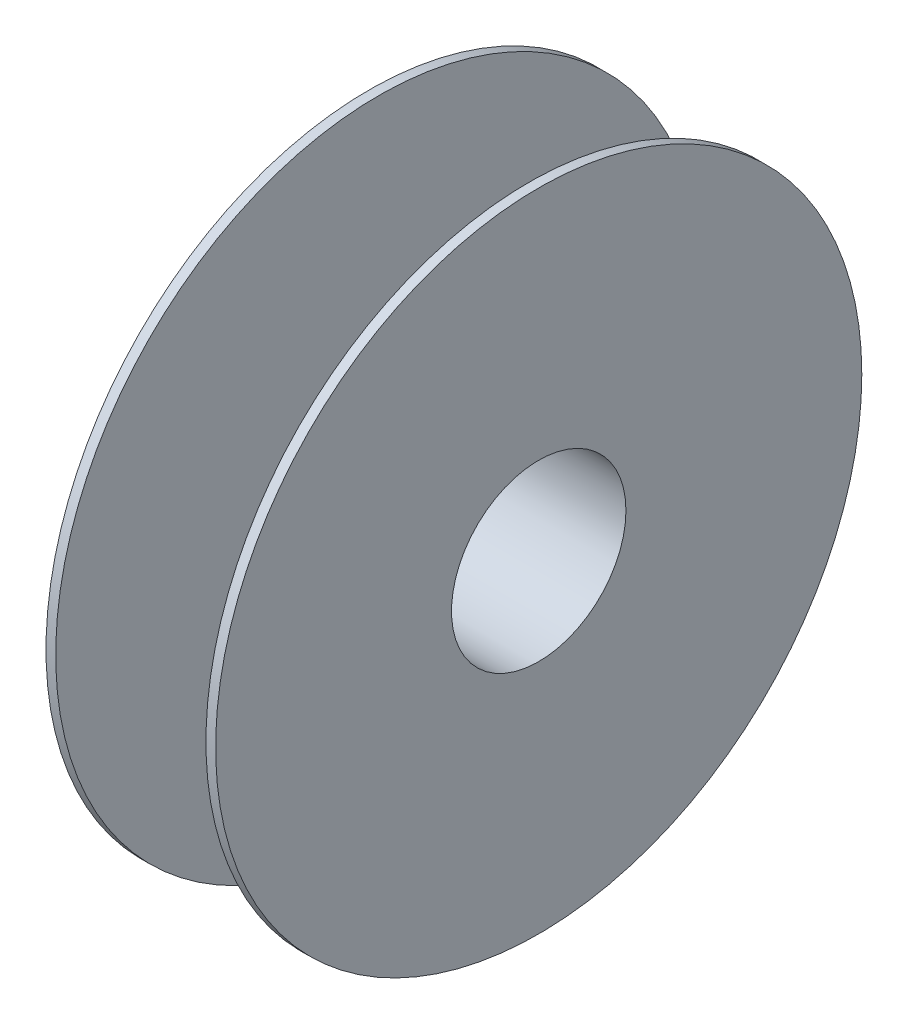
SolidWorks part; units mm, degrees
ref_plane "Front Plane" through (0, 0, 0) normal (0, 0, 1) x (1, 0, 0)
ref_plane "Top Plane" through (0, 0, 0) normal (0, 1, 0) x (1, 0, 0)
ref_plane "Right Plane" through (0, 0, 0) normal (1, 0, 0) x (0, 0, -1)
sketch "Sketch1" plane through (0, 0, 0) normal (0, 0, 1) x (1, 0, 0)
  line L0 (-26.25, 27) -> (-26.25, 100)
  line L1 (-26.25, 100) -> (-23.25, 100)
  line L2 (-23.25, 100) -> (-23.25, 30)
  line L3 (-23.25, 30) -> (23.25, 30)
  line L5 (26.25, 27) -> (-26.25, 27)
  line L6 (0, 0) -> (-53.3973, 0) construction
  line L7 (23.25, 30) -> (23.25, 100)
  line L8 (23.25, 100) -> (26.25, 100)
  line L9 (26.25, 100) -> (26.25, 27)
  line L10 (0, 0) -> (0, 43.7958) construction
  dimension "D1" = 200
  dimension "D2" = 52.5
  dimension "D3" = 3
  dimension "D4" = 73
  dimension "D5" = 3
revolve "Revolve1" add sketch "Sketch1" angle 360 about L6
